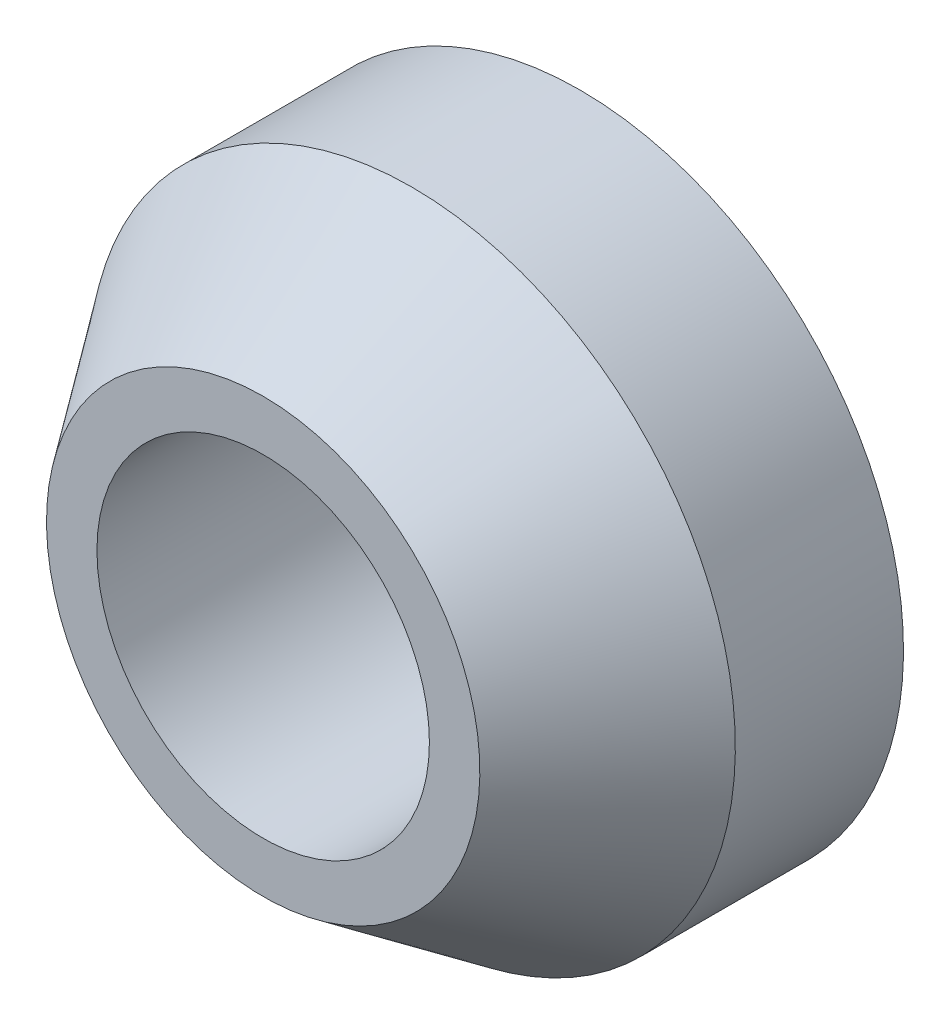
SolidWorks part; units mm, degrees
material "AISI 1045 Steel, cold drawn"
ref_plane "X-Y Datum" through (0, 0, 0) normal (0, 0, 1) x (1, 0, 0)
ref_plane "X-Z Datum" through (0, 0, 0) normal (0, 1, 0) x (1, 0, 0)
ref_plane "Y-Z Datum" through (0, 0, 0) normal (1, 0, 0) x (0, 0, -1)
sketch "Sketch1" plane through (0, 0, 0) normal (1, 0, 0) x (0, 0, -1)
  line L1 (-6.35, 0) -> (-6.35, 4.2545)
  line L2 (-6.35, 4.2545) -> (-3.429, 6.35)
  line L3 (-3.429, 6.35) -> (0, 6.35)
  line L4 (0, 6.35) -> (0, 0)
  line L5 (0, 0) -> (-6.35, 0)
  point P0 (0, 3.175)
  dimension "D1" = 6.35
  dimension "D2" = 6.35
  dimension "D3" = 4.2545
  dimension "D4" = 3.429
revolve "Revolve1" add sketch "Sketch1" angle 360 about L5
hole_wizard "1/4 Clearance Hole1" positions "Sketch2" profile "Sketch3" hole size "1/4" standard "ANSI Inch" end condition through all
sketch "Sketch2" plane through (0, 0, 6.35) normal (0, 0, 1) x (1, 0, 0)
  point P0 (0, 0)
sketch "Sketch3" plane through (0, 0, 6.35) normal (1, 0, 0) x (0, -1, 0)
  line L0 (0, 0) -> (0, 6.35)
  line L1 (0, 6.35) -> (3.2639, 6.35)
  line L2 (3.2639, 6.35) -> (3.2639, 0)
  line L5 (3.2639, 0) -> (0, 0)
  line L11 (0, -6.35) -> (0, 107.95) construction
  dimension "Thru Hole Dia." = 6.5278
  dimension "Thru Hole Depth" = 6.35
sketch "Sketch4" plane through (0, 0, 0) normal (0, 0, -1) x (-1, 0, 0)
  line L1 (-6.35, 6.35) -> (6.35, 6.35)
  line L2 (-6.35, 6.35) -> (-6.35, -6.35)
  line L3 (-6.35, -6.35) -> (6.35, -6.35)
  line L4 (6.35, 6.35) -> (6.35, -6.35)
  circle A0 centre (0, 0) radius 6.35 construction
  dimension "D1" = 12.7
extrude "Cut-Extrude1" cut sketch "Sketch4" against normal blind 0.127
